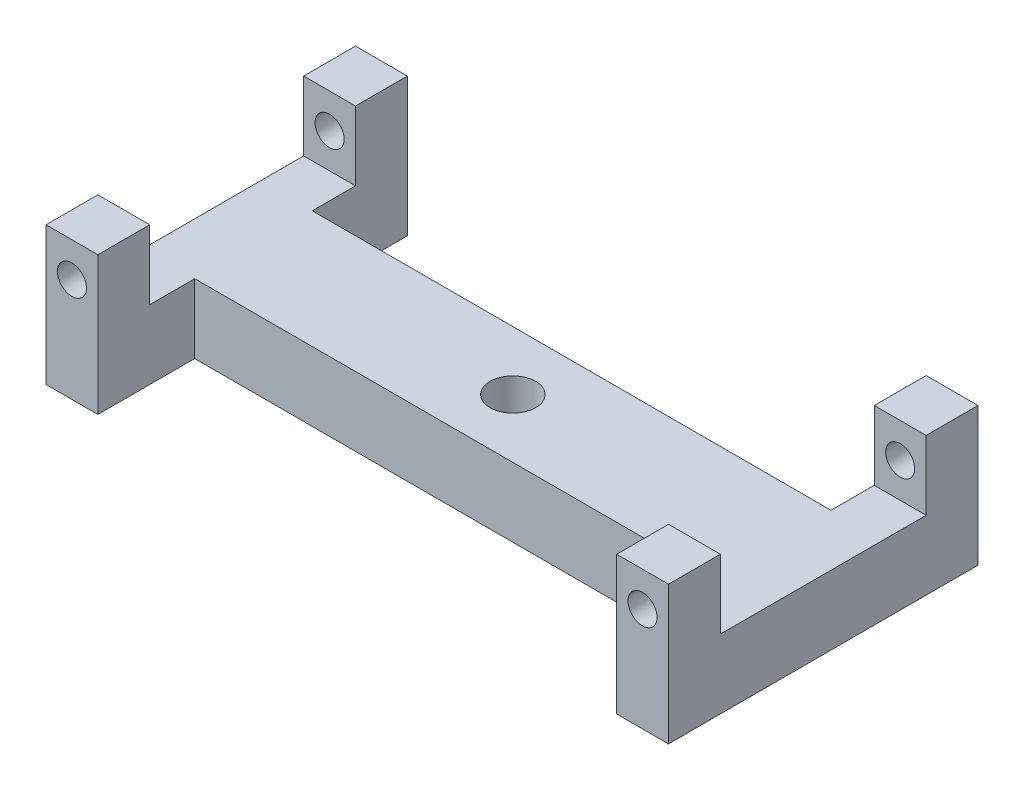
SolidWorks part; units mm, degrees
material "PVC Rigid"
ref_plane "Front Plane" through (0, 0, 0) normal (0, 0, 1) x (1, 0, 0)
ref_plane "Top Plane" through (0, 0, 0) normal (0, 1, 0) x (1, 0, 0)
ref_plane "Right Plane" through (0, 0, 0) normal (1, 0, 0) x (0, 0, -1)
sketch "Sketch1" plane through (0, 0, 0) normal (0, 1, 0) x (1, 0, 0)
  line L1 (-57.15, 10.795) -> (57.15, 10.795)
  line L2 (-57.15, 10.795) -> (-57.15, -10.795)
  line L3 (-57.15, -10.795) -> (57.15, -10.795)
  line L4 (57.15, 10.795) -> (57.15, -10.795)
  line L5 (-57.15, 10.795) -> (57.15, -10.795) construction
  line L6 (-57.15, -10.795) -> (57.15, 10.795) construction
  circle A1 centre (0, 0) radius 4.191
  point P0 (0, 0)
  dimension "D3" = 8.382
  dimension "D1" = 114.3
  dimension "D2" = 21.59
extrude "Boss-Extrude1" add sketch "Sketch1" along normal blind 6.35
sketch "Sketch2" plane through (0, 0, -10.795) normal (0, 0, -1) x (-1, 0, 0)
  line L0 (-57.15, 0) -> (57.15, 0) construction
  line L1 (-57.15, 6.35) -> (-47.625, 6.35)
  line L2 (-57.15, 6.35) -> (-57.15, 0)
  line L3 (-57.15, 0) -> (-47.625, 0)
  line L4 (-47.625, 6.35) -> (-47.625, 0)
  dimension "D1" = 9.525
extrude "Boss-Extrude2" add sketch "Sketch2" along normal blind 17.4625
sketch "Sketch3" plane through (0, 0, -10.795) normal (0, 0, -1) x (-1, 0, 0)
  line L0 (-47.625, 0) -> (57.15, 0) construction
  line L1 (57.15, 6.35) -> (47.625, 6.35)
  line L2 (57.15, 6.35) -> (57.15, 0)
  line L3 (57.15, 0) -> (47.625, 0)
  line L4 (47.625, 6.35) -> (47.625, 0)
  dimension "D1" = 9.525
extrude "Boss-Extrude3" add sketch "Sketch3" along normal blind 17.4625
sketch "Sketch4" plane through (0, 0, 10.795) normal (0, 0, 1) x (1, 0, 0)
  line L0 (-57.15, 0) -> (57.15, 0) construction
  line L1 (-57.15, 6.35) -> (-47.625, 6.35)
  line L2 (-57.15, 6.35) -> (-57.15, 0)
  line L3 (-57.15, 0) -> (-47.625, 0)
  line L4 (-47.625, 6.35) -> (-47.625, 0)
  line L6 (57.15, 6.35) -> (47.625, 6.35)
  line L7 (57.15, 6.35) -> (57.15, 0)
  line L8 (57.15, 0) -> (47.625, 0)
  line L9 (47.625, 6.35) -> (47.625, 0)
  dimension "D1" = 9.525
extrude "Boss-Extrude4" add sketch "Sketch4" along normal blind 17.78
sketch "Sketch6" plane through (0, 6.35, 0) normal (0, 1, 0) x (1, 0, 0)
  line L0 (-47.625, -28.575) -> (-47.625, -10.795) construction
  line L1 (-57.15, 28.2575) -> (-47.625, 28.2575)
  line L2 (-57.15, 28.2575) -> (-57.15, 18.7325)
  line L3 (-57.15, 18.7325) -> (-47.625, 18.7325)
  line L4 (-47.625, 28.2575) -> (-47.625, 18.7325)
  line L5 (-57.15, -28.575) -> (-47.625, -28.575)
  line L6 (-57.15, -28.575) -> (-57.15, -19.05)
  line L7 (-57.15, -19.05) -> (-47.625, -19.05)
  line L8 (-47.625, -28.575) -> (-47.625, -19.05)
  line L9 (57.15, -28.575) -> (57.15, 28.2575) construction
  line L10 (47.625, 28.2575) -> (57.15, 28.2575)
  line L11 (47.625, 28.2575) -> (47.625, 18.7325)
  line L12 (47.625, 18.7325) -> (57.15, 18.7325)
  line L13 (57.15, 28.2575) -> (57.15, 18.7325)
  line L14 (47.625, -28.575) -> (47.625, -10.795) construction
  line L15 (57.15, -28.575) -> (47.625, -28.575)
  line L16 (57.15, -28.575) -> (57.15, -19.05)
  line L17 (57.15, -19.05) -> (47.625, -19.05)
  line L18 (47.625, -28.575) -> (47.625, -19.05)
  line L19 (-47.625, 28.2575) -> (-47.625, 10.795) construction
extrude "Boss-Extrude5" add sketch "Sketch6" along normal blind 12.7
sketch "Sketch7" plane through (0, 0, -28.2575) normal (0, 0, -1) x (-1, 0, 0)
  line L0 (-57.15, 19.05) -> (-47.625, 19.05) construction
  line L1 (47.625, 19.05) -> (57.15, 19.05) construction
  circle A0 centre (-52.3875, 12.7) radius 2.667
  circle A1 centre (52.3875, 12.7) radius 2.667
  point P5 (-52.3875, 19.05)
  point P9 (52.3875, 19.05)
  dimension "D1" = 5.334
  dimension "D2" = 6.35
extrude "Cut-Extrude1" cut sketch "Sketch7" against normal blind 92.456 and the other way blind 53.848
sketch "Sketch9" plane through (0, 0, 0) normal (0, -1, 0) x (1, 0, 0)
  line L12 (57.15, -28.2575) -> (57.15, 28.575)
  line L13 (57.15, 28.575) -> (47.625, 28.575)
  line L14 (47.625, 28.575) -> (47.625, 10.795)
  line L15 (47.625, 10.795) -> (-47.625, 10.795)
  line L16 (-47.625, 10.795) -> (-47.625, 28.575)
  line L17 (-47.625, 28.575) -> (-57.15, 28.575)
  line L18 (-57.15, 28.575) -> (-57.15, -28.2575)
  line L19 (-57.15, -28.2575) -> (-47.625, -28.2575)
  line L20 (-47.625, -28.2575) -> (-47.625, -10.795)
  line L21 (-47.625, -10.795) -> (47.625, -10.795)
  line L22 (47.625, -10.795) -> (47.625, -28.2575)
  line L23 (47.625, -28.2575) -> (57.15, -28.2575)
  line L24 (57.15, -28.2575) -> (57.15, 28.575)
  line L25 (57.15, 28.575) -> (47.625, 28.575)
  line L26 (47.625, 28.575) -> (47.625, 10.795)
  line L27 (47.625, 10.795) -> (-47.625, 10.795)
  line L28 (-47.625, 10.795) -> (-47.625, 28.575)
  line L29 (-47.625, 28.575) -> (-57.15, 28.575)
  line L30 (-57.15, 28.575) -> (-57.15, -28.2575)
  line L31 (-57.15, -28.2575) -> (-47.625, -28.2575)
  line L32 (-47.625, -28.2575) -> (-47.625, -10.795)
  line L33 (-47.625, -10.795) -> (47.625, -10.795)
  line L34 (47.625, -10.795) -> (47.625, -28.2575)
  line L35 (47.625, -28.2575) -> (57.15, -28.2575)
  dimension "D1" = 0
extrude "Boss-Extrude6" add sketch "Sketch9" along normal blind 6.35
sketch "Sketch10" plane through (0, 0, 0) normal (0, 1, 0) x (1, 0, 0)
  circle A0 centre (0, 0) radius 4.191
  dimension "D1" = 8.382
extrude "Cut-Extrude2" cut sketch "Sketch10" against normal up to surface (6.35 mm away) up to face at (0, -6.35, 0.1058)
sketch "Sketch11" plane through (0, -6.35, 0) normal (0, -1, 0) x (1, 0, 0)
  circle A0 centre (0, 0) radius 7.1438
  dimension "D1" = 14.2875
extrude "Cut-Extrude3" cut sketch "Sketch11" against normal blind 6.7312
